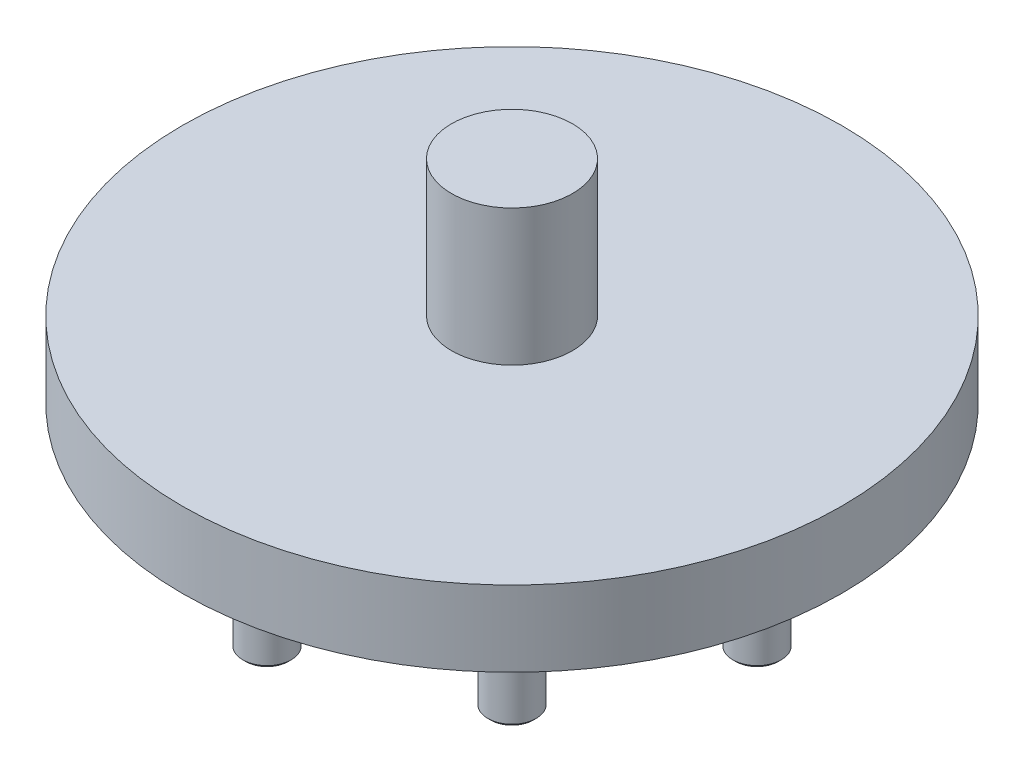
SolidWorks part; units mm, degrees
ref_plane "Front Plane" through (0, 0, 0) normal (0, 0, 1) x (1, 0, 0)
ref_plane "Top Plane" through (0, 0, 0) normal (0, 1, 0) x (1, 0, 0)
ref_plane "Right Plane" through (0, 0, 0) normal (1, 0, 0) x (0, 0, -1)
sketch "Sketch1" plane through (0, 0, 0) normal (0, 0, 1) x (1, 0, 0)
  line L0 (0, 0) -> (0, 112.5)
  line L1 (0, 112.5) -> (30, 112.5)
  line L2 (30, 112.5) -> (30, 45)
  line L3 (30, 45) -> (163.5, 45)
  line L4 (163.5, 45) -> (163.5, 7.5)
  line L5 (163.5, 7.5) -> (79.5, 7.5)
  line L6 (79.5, 7.5) -> (79.5, 0)
  line L7 (79.5, 0) -> (0, 0)
  dimension "D1" = 112.5
  dimension "D2" = 30
  dimension "D3" = 67.5
  dimension "D4" = 37.5
  dimension "D5" = 84
  dimension "D6" = 79.5
revolve "Revolve1" add sketch "Sketch1" angle 360 about L0
sketch "Sketch2" plane through (0, 7.5, 0) normal (0, -1, 0) x (1, 0, 0)
  circle A0 centre (121.5, 0) radius 12
  dimension "D1" = 24
  dimension "D2" = 121.5
extrude "Boss-Extrude1" add sketch "Sketch2" along normal blind 45 contours A0
chamfer "Chamfer1" distance 1.5 angle 45 1 edges at (121.5, -37.5, -12)
pattern_circular "CirPattern1" count 8 over 360 about axis through (0, 0, 0) along (0, 1, 0) of "Chamfer1", "Boss-Extrude1"
